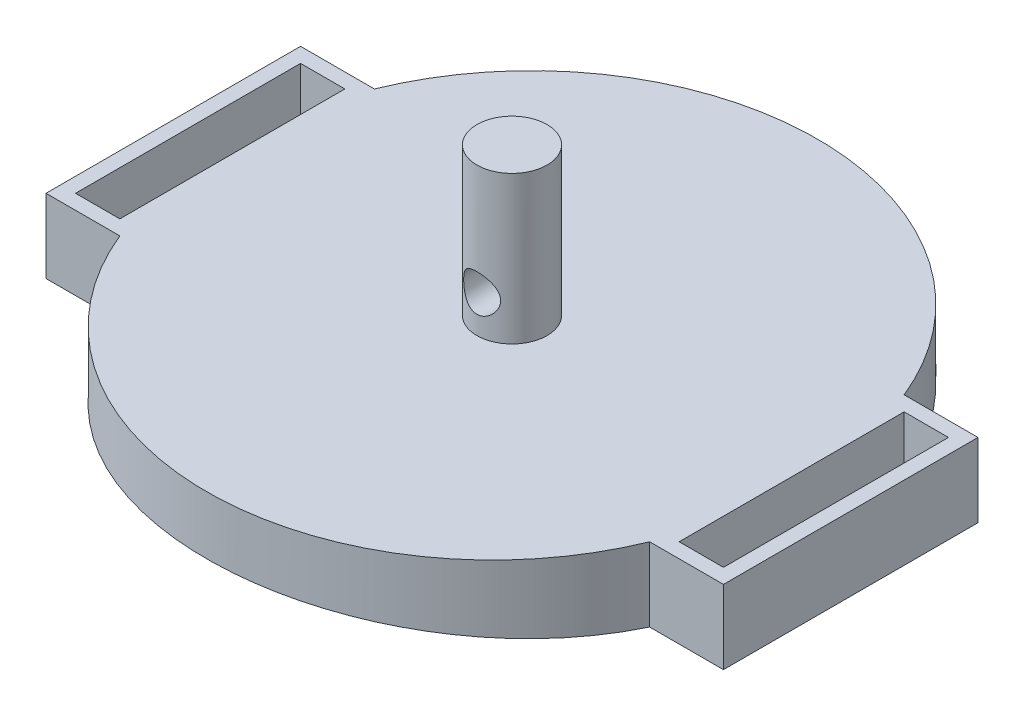
SolidWorks part; units mm, degrees
ref_plane "Front Plane" through (0, 0, 0) normal (0, 0, 1) x (1, 0, 0)
ref_plane "Top Plane" through (0, 0, 0) normal (0, 1, 0) x (1, 0, 0)
ref_plane "Right Plane" through (0, 0, 0) normal (1, 0, 0) x (0, 0, -1)
sketch "Sketch4" plane through (0, 0, 0) normal (0, 1, 0) x (1, 0, 0)
  line L1 (0, -55) -> (0, 55) construction
  line L3 (-52.8407, -31.5076) -> (52.8407, -31.5076) construction
  line L4 (0, 9.8422) -> (0, -72.8575) construction
  line L6 (35.8579, -48.7381) -> (45.8579, -48.7381)
  line L7 (35.8579, -14.2772) -> (45.8579, -14.2772)
  line L8 (45.8579, -48.7381) -> (45.8579, -14.2772)
  line L9 (-35.8579, -14.2772) -> (-45.8579, -14.2772)
  line L10 (-45.8579, -48.7381) -> (-45.8579, -14.2772)
  line L11 (-35.8579, -48.7381) -> (-45.8579, -48.7381)
  line L12 (-35.8579, -48.7381) -> (-35.8579, -14.2772) construction
  line L13 (37.8579, -46.7381) -> (37.8579, -16.2772)
  line L14 (-43.8579, -46.7381) -> (-37.8579, -46.7381)
  line L15 (-43.8579, -46.7381) -> (-43.8579, -16.2772)
  line L16 (-43.8579, -16.2772) -> (-37.8579, -16.2772)
  line L17 (-37.8579, -46.7381) -> (-37.8579, -16.2772)
  line L18 (43.8579, -16.2772) -> (37.8579, -16.2772)
  line L19 (43.8579, -46.7381) -> (43.8579, -16.2772)
  line L20 (43.8579, -46.7381) -> (37.8579, -46.7381)
  arc A1 (-35.8579, -48.7381) -> (35.8579, -48.7381) centre (0, -34.143) ccw
  arc A2 (-35.8579, -14.2772) -> (35.8579, -14.2772) centre (0, -28.8723) cw
  dimension "D2" = 34.461
  dimension "D3" = 2
  dimension "D1" = 2
  dimension "D4" = 2
  dimension "D5" = 10
  dimension "D6" = 2
  dimension "D7" = 10
extrude "Boss-Extrude3" add sketch "Sketch4" along normal blind 10
sketch "Sketch5" plane through (0, 10, 0) normal (0, 1, 0) x (1, 0, 0)
  line L0 (0, 9.8422) -> (0, -72.8575) construction
  line L1 (-52.8407, -44.8867) -> (52.8407, -44.8867) construction
  line L2 (-52.8407, -27.6562) -> (-52.8407, -62.1172) construction
  line L3 (52.8407, -62.1172) -> (52.8407, -27.6562) construction
  arc A0 (35.8579, -14.2772) -> (-35.8579, -14.2772) centre (0, -28.8723) ccw construction
  arc A1 (-35.8579, -48.7381) -> (35.8579, -48.7381) centre (0, -34.143) ccw construction
  circle A2 centre (0, -31.5076) radius 4.75
  dimension "D1" = 9.5
extrude "Boss-Extrude4" add sketch "Sketch5" along normal blind 20
ref_plane "Plane1" through (0, 0, 26.7576) normal (0, 0, -1) x (-1, 0, 0)
sketch "Sketch6" plane through (0, 0, 26.7576) normal (0, 0, -1) x (-1, 0, 0)
  line L0 (35.8579, 10) -> (-35.8579, 10) construction
  circle A0 centre (0, 15) radius 2.5
  dimension "D1" = 5
  dimension "D2" = 5
extrude "Cut-Extrude1" cut sketch "Sketch6" against normal up to next
ref_plane "Plane2" through (0, 0, 72.8575) normal (0, 0, 1) x (1, 0, 0)
sketch "Sketch7" plane through (0, 0, 72.8575) normal (0, 0, 1) x (1, 0, 0)
  line L0 (-35.8579, 0) -> (35.8579, 0)
  arc A0 (-35.8579, 0) -> (35.8579, 0) centre (0, -301.1037) cw
extrude "Cut-Extrude2" cut sketch "Sketch7" against normal up to next
